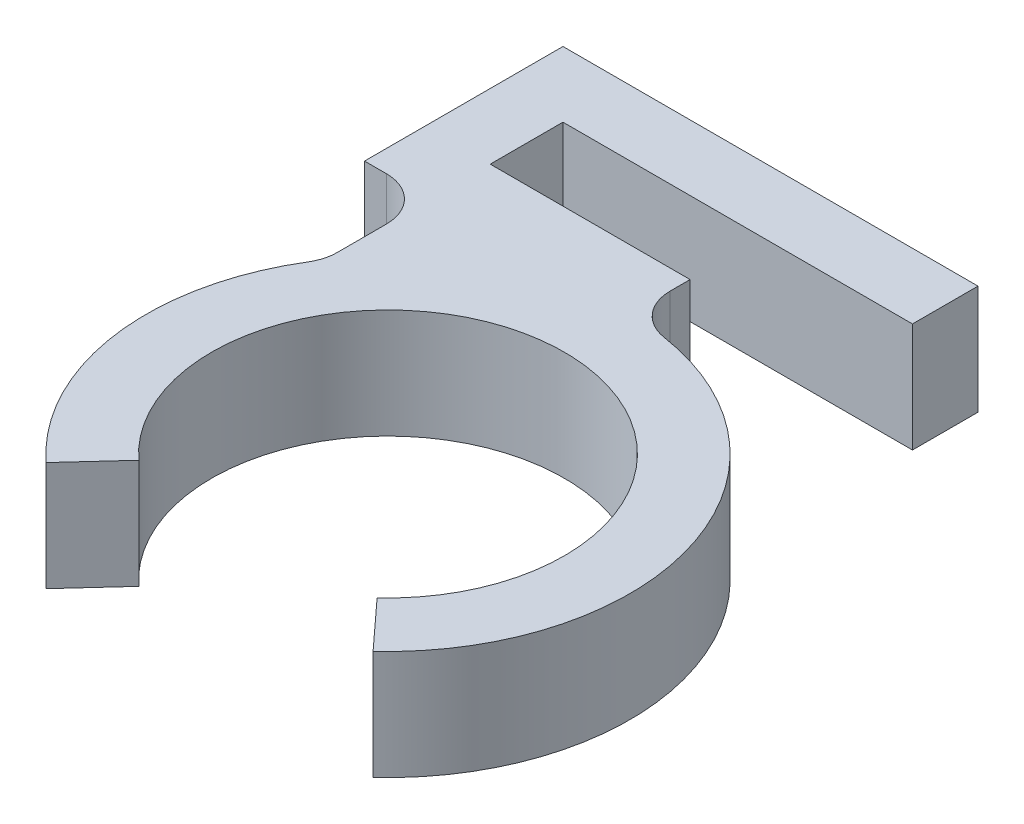
SolidWorks part; units mm, degrees
ref_plane "Front Plane" through (0, 0, 0) normal (0, 0, 1) x (1, 0, 0)
ref_plane "Top Plane" through (0, 0, 0) normal (0, 1, 0) x (1, 0, 0)
ref_plane "Right Plane" through (0, 0, 0) normal (1, 0, 0) x (0, 0, -1)
sketch "Sketch1" plane through (0, 0, 0) normal (0, 1, 0) x (1, 0, 0)
  line L0 (4.6678, -28.3253) -> (6.6946, -26.1135)
  line L1 (0, 0) -> (19, 0)
  line L2 (0, 0) -> (0, -9.085)
  line L3 (3, -3) -> (19, -3)
  line L4 (19, 0) -> (19, -3)
  line L5 (19.6322, -28.3253) -> (17.6054, -26.1135)
  line L6 (3, -11.085) -> (3, -13.3312)
  line L9 (0, -9.085) -> (1, -9.085)
  line L10 (3, -3) -> (3, -6.33)
  line L13 (3, -6.33) -> (12.15, -6.33)
  line L15 (4.6678, -28.3253) -> (19.6322, -28.3253) construction
  line L16 (12.15, -6.33) -> (12.15, -7.2389)
  arc A0 (17.6054, -26.1135) -> (6.6946, -26.1135) centre (12.15, -20.16) ccw
  arc A1 (4.6678, -28.3253) -> (2.7055, -14.3757) centre (12.15, -20.16) cw
  arc A2 (13.8441, -9.2153) -> (19.6322, -28.3253) centre (12.15, -20.16) cw
  arc A3 (3, -13.9204) -> (12.15, -9.085) centre (12.15, -20.16) cw construction
  arc A4 (3, -13.3312) -> (2.7055, -14.3757) centre (1, -13.3312) cw
  arc A5 (3, -11.085) -> (1, -9.085) centre (1, -11.085) ccw
  arc A6 (12.15, -7.2389) -> (13.8441, -9.2153) centre (14.15, -7.2389) ccw
  point P26 (12.15, -9.085)
  dimension "D3" = 8.075
  dimension "D10" = 2
  dimension "D2" = 13.83
  dimension "D5" = 3.33
  dimension "D8" = 3
  dimension "D1" = 3
  dimension "D4" = 3
  dimension "D6" = 9.15
  dimension "D7" = 16
  dimension "D9" = 275
extrude "Boss-Extrude1" add sketch "Sketch1" along normal blind 5
equation "\"motor_radius\"= 8mm"
equation "\"D2@Sketch1\"=\"motor_to_crossbar_base\""
equation "\"D3@Sketch1\"=\"motor_radius\"+\"tolerance\"/2"
equation "\"motor_to_crossbar_edge\"= 9mm"
equation "\"motor_to_crossbar_base\"= 13.83mm"
equation "\"crossbar_height\"= 3.18mm"
equation "\"tolerance\"= 0.15mm"
equation "\"D5@Sketch1\"=\"crossbar_height\"+\"tolerance\""
equation "\"D6@Sketch1\"=\"motor_to_crossbar_edge\"+\"tolerance\""
